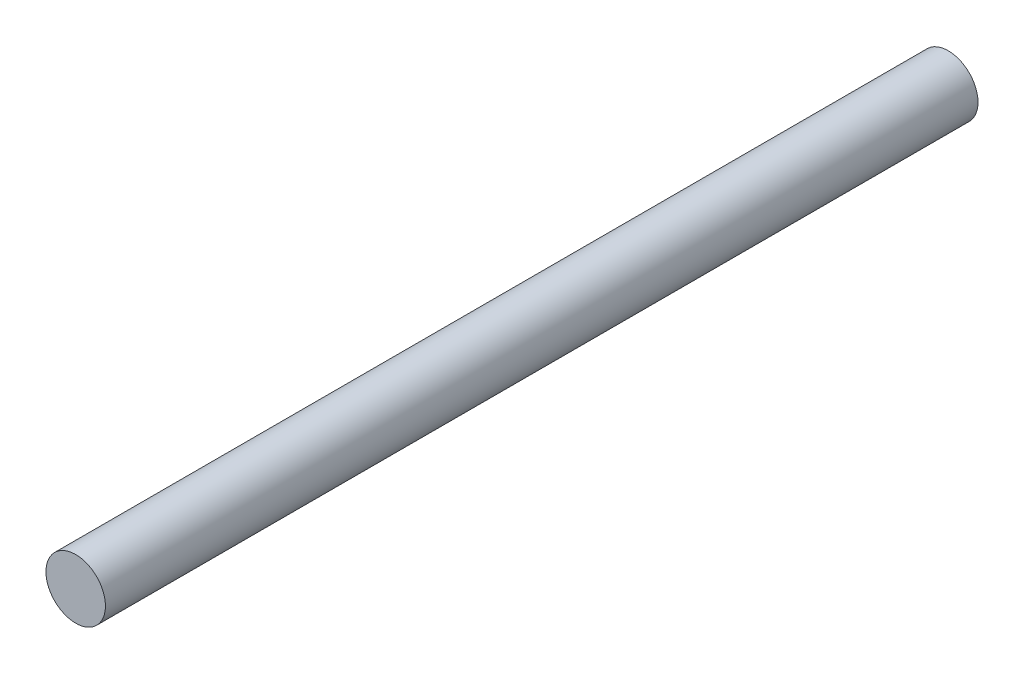
SolidWorks part; units mm, degrees
ref_plane "Front Plane" through (0, 0, 0) normal (0, 0, 1) x (1, 0, 0)
ref_plane "Top Plane" through (0, 0, 0) normal (0, 1, 0) x (1, 0, 0)
ref_plane "Right Plane" through (0, 0, 0) normal (1, 0, 0) x (0, 0, -1)
ref_plane "Plane1"
sketch "Sketch1" plane through (0, 0, 0) normal (0, 0, 1) x (1, 0, 0)
  circle A0 centre (0, 0) radius 1.5
extrude "Extrusion1" add sketch "Sketch1" along normal blind 44
